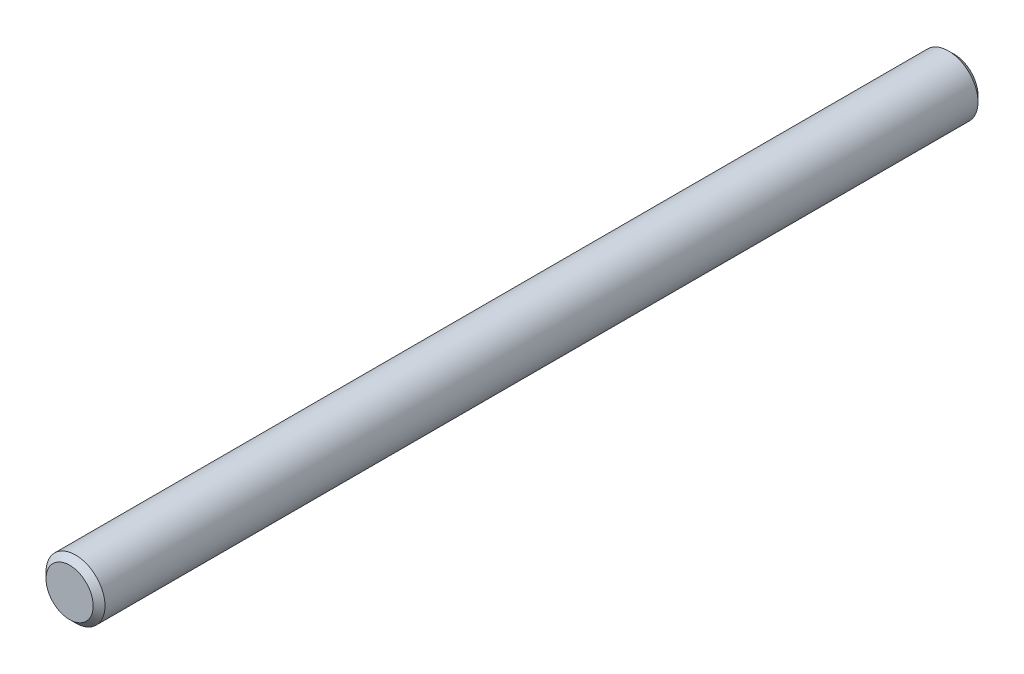
SolidWorks part; units mm, degrees
ref_plane "Plano frontal" through (0, 0, 0) normal (0, 0, 1) x (1, 0, 0)
ref_plane "Plano superior" through (0, 0, 0) normal (0, 1, 0) x (1, 0, 0)
ref_plane "Plano direito" through (0, 0, 0) normal (1, 0, 0) x (0, 0, -1)
sketch "Esboço1" plane through (0, 0, 0) normal (0, 0, 1) x (1, 0, 0)
  circle A0 centre (0, 0) radius 2.5
  dimension "D1" = 5
extrude "Ressalto-extrusão1" add sketch "Esboço1" along normal blind 75
ref_plane "Plano1" through (0, 0, 53) normal (0, 0, 1) x (1, 0, 0)
chamfer "Chanfro1" distance 0.5 angle 45 2 edges at (2.5, 0, 0) (2.5, 0, 75)
